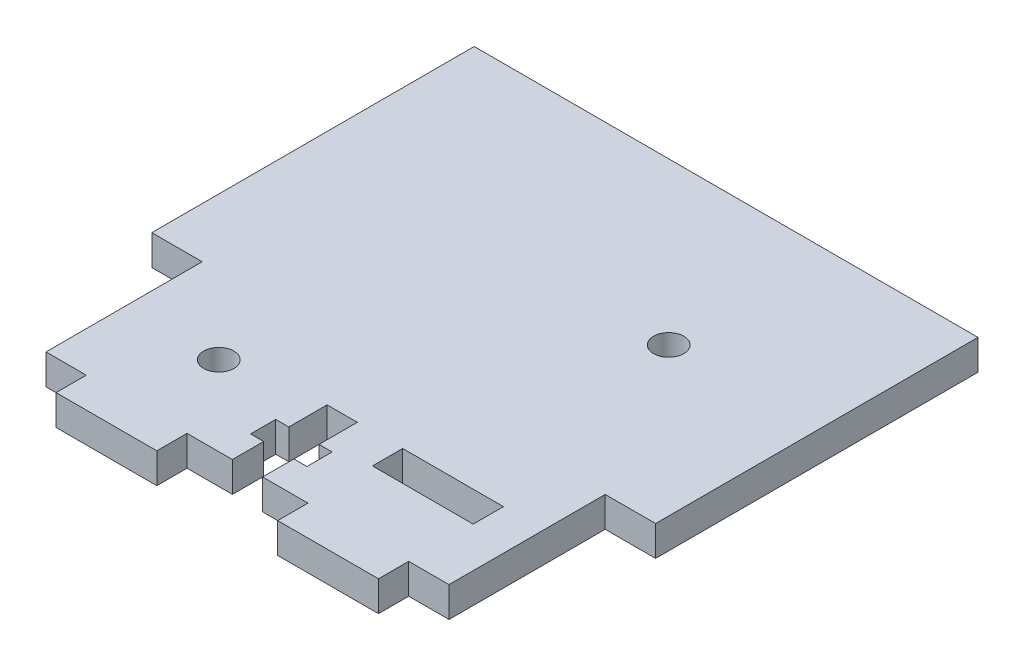
SolidWorks part; units mm, degrees
ref_plane "Front Plane" through (0, 0, 0) normal (0, 0, 1) x (1, 0, 0)
ref_plane "Top Plane" through (0, 0, 0) normal (0, 1, 0) x (1, 0, 0)
ref_plane "Right Plane" through (0, 0, 0) normal (1, 0, 0) x (0, 0, -1)
sketch "Sketch2" plane through (0, 0, 0) normal (0, 1, 0) x (1, 0, 0)
  line L0 (0, 15.5) -> (5, 15.5)
  line L1 (0, 0) -> (-4, 0)
  line L2 (0, 0) -> (0, 15.5)
  line L4 (-40, 0) -> (-40, 15.5)
  line L5 (5, 15.5) -> (5, 47.5)
  line L7 (-45, 47.5) -> (-45, 15.5)
  line L8 (-45, 15.5) -> (-40, 15.5)
  line L9 (-20, 47.5) -> (-20, 9.4) construction
  line L15 (5, 47.5) -> (-45, 47.5)
  line L16 (-4, 0) -> (-4, -3)
  line L17 (-4, -3) -> (-14, -3)
  line L18 (-14, -3) -> (-14, 0)
  line L19 (-14, 0) -> (-18.5, 0)
  line L20 (-26, -3) -> (-26, 0)
  line L21 (-36, -3) -> (-26, -3)
  line L22 (-36, 0) -> (-36, -3)
  line L23 (-36, 0) -> (-40, 0)
  line L25 (-18.5, 0) -> (-18.5, 3.1)
  line L26 (-18.5, 3.1) -> (-17.2, 3.1)
  line L27 (-17.2, 3.1) -> (-17.2, 5.6)
  line L28 (-17.2, 5.6) -> (-18.5, 5.6)
  line L29 (-18.5, 5.6) -> (-18.5, 9.4)
  line L30 (-18.5, 9.4) -> (-21.5, 9.4)
  line L31 (-21.5, 9.4) -> (-21.5, 5.6)
  line L32 (-21.5, 5.6) -> (-22.8, 5.6)
  line L33 (-22.8, 5.6) -> (-22.8, 3.1)
  line L34 (-22.8, 3.1) -> (-21.5, 3.1)
  line L35 (-21.5, 3.1) -> (-21.5, 0)
  line L36 (-21.5, 0) -> (-26, 0)
  line L44 (-14, 6.4) -> (-4, 6.4)
  line L45 (-4, 6.4) -> (-4, 9.4)
  line L46 (-4, 9.4) -> (-14, 9.4)
  line L47 (-14, 9.4) -> (-14, 6.4)
  circle A7 centre (-30.75, 7.9) radius 1.5
  circle A8 centre (-9.7, 31.5) radius 1.5
  point P10 (-20, 47.5)
  point P23 (-4, 0)
  point P52 (-14, 7.9)
  dimension "D6" = 16
  dimension "D7" = 9.7
  dimension "D8" = 9.25
  dimension "D4" = 3
  dimension "D1" = 15.5
  dimension "D2" = 40
  dimension "D3" = 5
  dimension "D5" = 32
  dimension "D11" = 4
  dimension "D12" = 10
  dimension "D13" = 3
  dimension "D14" = 1.3
  dimension "D15" = 3.1
  dimension "D16" = 2.5
  dimension "D17" = 3.8
  dimension "D18" = 3
  dimension "D19" = 4.5
extrude "Boss-Extrude1" add sketch "Sketch2" along normal blind 3
